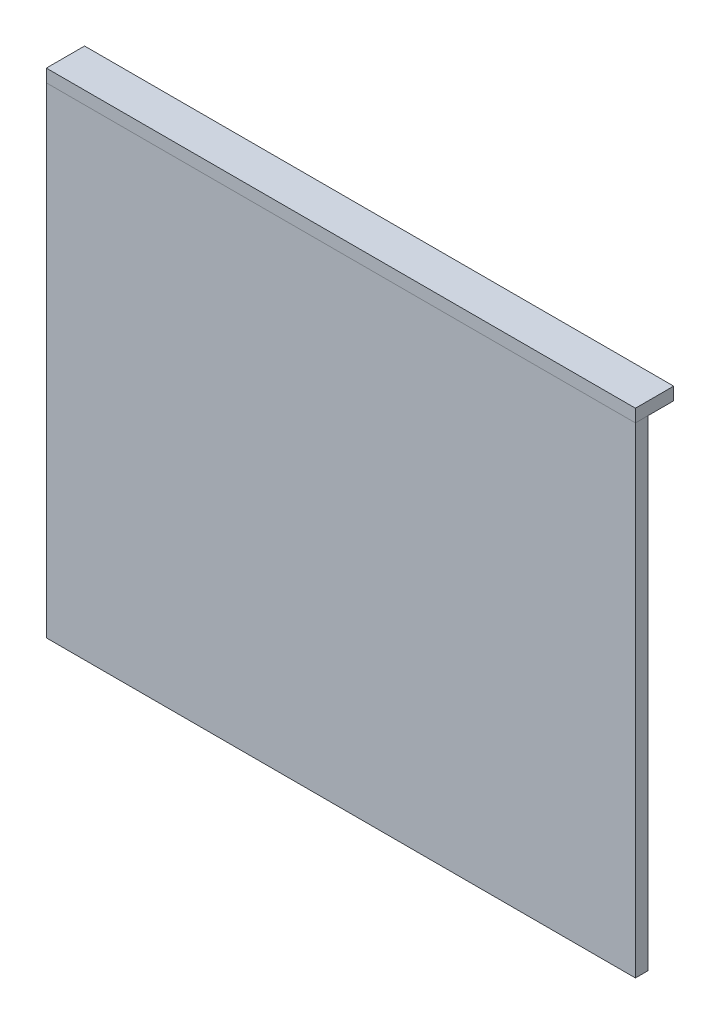
SolidWorks part; units mm, degrees
ref_plane "Front Plane" through (0, 0, 0) normal (0, 0, 1) x (1, 0, 0)
ref_plane "Top Plane" through (0, 0, 0) normal (0, 1, 0) x (1, 0, 0)
ref_plane "Right Plane" through (0, 0, 0) normal (1, 0, 0) x (0, 0, -1)
sketch "Sketch1" plane through (0, 0, 0) normal (0, 0, 1) x (1, 0, 0)
  line L0 (1081.9039, 640.7969) -> (1081.9039, 162.0069)
  line L1 (1081.9039, 749.5089) -> (1081.9039, 162.0069) construction
  line L2 (1081.9039, 162.0069) -> (1668.6439, 162.0069)
  line L3 (1668.6439, 162.0069) -> (1668.6439, 640.7969)
  line L5 (1081.9039, 640.7969) -> (1668.6439, 640.7969)
  dimension "D1" = 478.79
  dimension "D2" = 586.74
extrude "Boss-Extrude1" add sketch "Sketch1" against normal blind 12.7
sketch "Sketch2" plane through (0, 640.7969, 0) normal (0, 1, 0) x (1, 0, 0)
  line L0 (1081.9039, 0) -> (1081.9039, 38.1)
  line L2 (1081.9039, 38.1) -> (1668.6439, 38.1)
  line L4 (1668.6439, 38.1) -> (1668.6439, 0)
  line L5 (1668.6439, 0) -> (1081.9039, 0)
  dimension "D1" = 38.1
extrude "Boss-Extrude2" add sketch "Sketch2" along normal blind 12.7 separate body
equation "\"FRAME_LARGE_FACE_HEIGHT\"= 18.85"
equation "\"D1@Sketch1\"=\"FRAME_LARGE_FACE_HEIGHT\""
equation "\"FRAME_SIDE_LENGTH\"=23.1"
equation "\"D2@Sketch1\"=\"FRAME_SIDE_LENGTH\""
equation "\"WOOD_THICKNESS\"=0.5"
equation "\"D1@Boss-Extrude1\"=\"WOOD_THICKNESS\""
equation "\"FRAME_SMALL_FACE_WIDTH\"=1.5"
equation "\"D1@Sketch2\"=\"FRAME_SMALL_FACE_WIDTH\""
equation "\"D1@Boss-Extrude2\"=\"WOOD_THICKNESS\""
